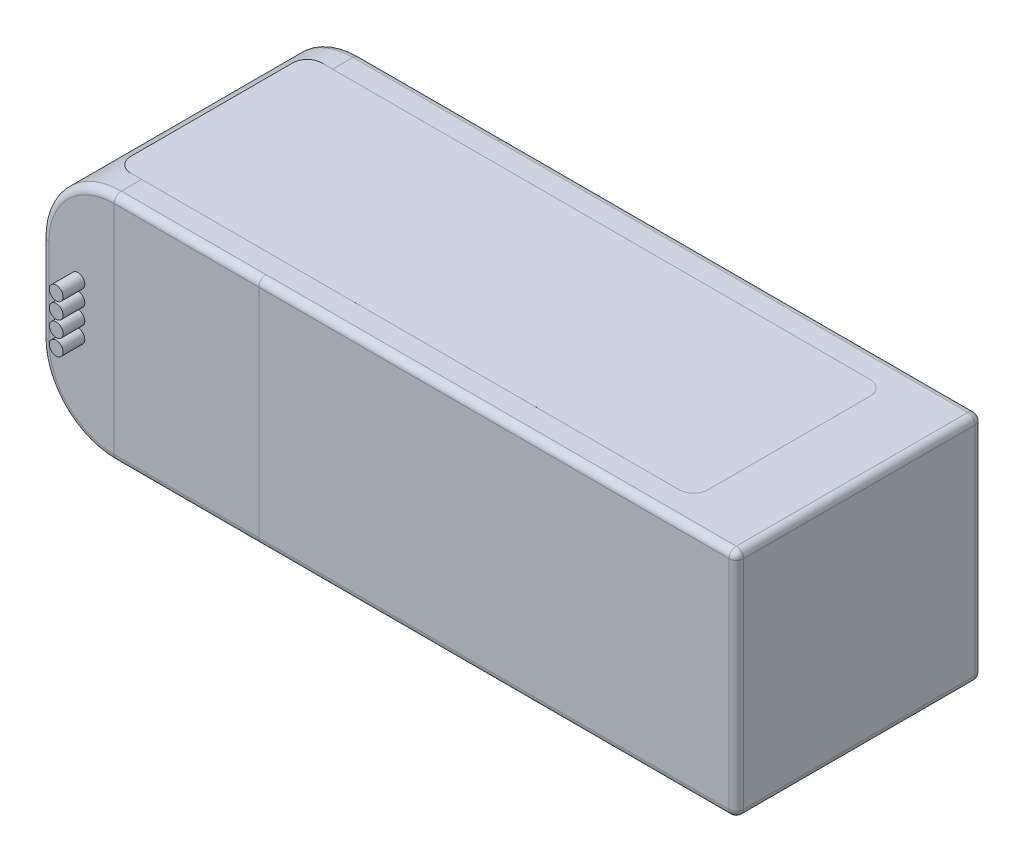
SolidWorks part; units mm, degrees
material "1060 Alloy"
ref_plane "Plano frontal" through (0, 0, 0) normal (0, 0, 1) x (1, 0, 0)
ref_plane "Plano superior" through (0, 0, 0) normal (0, 1, 0) x (1, 0, 0)
ref_plane "Plano direito" through (0, 0, 0) normal (1, 0, 0) x (0, 0, -1)
sketch "Sketch1" plane through (0, 0, 0) normal (0, 1, 0) x (1, 0, 0)
  line L1 (-48, 17) -> (48, 17)
  line L2 (-48, 17) -> (-48, -17)
  line L3 (-48, -17) -> (48, -17)
  line L4 (48, 17) -> (48, -17)
  point P4 (0, 17)
  point P6 (-48, 0)
  dimension "D1" = 34
  dimension "D2" = 96
extrude "Boss-Extrude1" add sketch "Sketch1" along normal mid plane 32
fillet "Fillet1" radius 10 2 edges at (-48, -16, 0) (-48, 16, 0)
sketch "Sketch2" plane through (0, 0, -17) normal (0, 0, -1) x (-1, 0, 0)
  line L1 (40, 1.45) -> (40, -1.45) construction
  line L2 (48, 6) -> (48, -6) construction
  circle A0 centre (40, 3.35) radius 1.9
  circle A1 centre (40, -3.35) radius 1.9
  point P4 (40, 0)
  dimension "D1" = 3.8
  dimension "D2" = 2.9
  dimension "D3" = 8
extrude "Boss-Extrude2" add sketch "Sketch2" along normal blind 5
sketch "Sketch4" plane through (0, 0, 17) normal (0, 0, 1) x (1, 0, 0)
  line L0 (-43, 4.25) -> (-43, -4.25) construction
  line L1 (-48, 6) -> (-48, -6) construction
  circle A0 centre (-43, 3.3) radius 0.95
  circle A1 centre (-43, 1.1) radius 0.95
  circle A2 centre (-43, -1.1) radius 0.95
  circle A3 centre (-43, -3.3) radius 0.95
  point P2 (-43, 0)
  dimension "D1" = 1.9
  dimension "D3" = 5
  dimension "D4" = 0.3
  dimension "D2" = 4
extrude "Boss-Extrude3" add sketch "Sketch4" along normal blind 3
sketch "Sketch5" plane through (0, 0, 17) normal (0, 0, 1) x (1, 0, 0)
  line L0 (-38, -16) -> (48, -16) construction
  line L1 (-38, 16) -> (-18, 16)
  line L2 (-38, 16) -> (-38, -16)
  line L3 (-38, -16) -> (-18, -16)
  line L4 (-18, 16) -> (-18, -16)
  dimension "D1" = 20
extrude "Boss-Extrude4" add sketch "Sketch5" along normal blind 0.0001
mirror "Mirror1" about plane through (0, 0, 0) normal (0, 0, 1) of "Boss-Extrude4" second plane through (0, 0, 0) second plane normal (0, 1, 0)
sketch "Sketch6" plane through (0, 16, 0) normal (0, 1, 0) x (1, 0, 0)
  line L0 (48, -17) -> (48, 17) construction
  line L1 (-39.5, 13.2) -> (36.3, 13.2)
  line L2 (-41.5, 11.2) -> (-41.5, -11.2)
  line L3 (-39.5, -13.2) -> (36.3, -13.2)
  line L4 (38.3, 11.2) -> (38.3, -11.2)
  arc A0 (36.3, 13.2) -> (38.3, 11.2) centre (36.3, 11.2) cw
  arc A1 (36.3, -13.2) -> (38.3, -11.2) centre (36.3, -11.2) ccw
  arc A2 (-41.5, -11.2) -> (-39.5, -13.2) centre (-39.5, -11.2) ccw
  arc A3 (-39.5, 13.2) -> (-41.5, 11.2) centre (-39.5, 11.2) ccw
  point P4 (-41.5, 0)
  point P10 (38.3, 13.2)
  point P15 (-41.5, -13.2)
  point P18 (-41.5, 13.2)
  dimension "D4" = 2
  dimension "D1" = 79.8
  dimension "D2" = 26.4
  dimension "D3" = 9.7
extrude "Boss-Extrude5" add sketch "Sketch6" along normal blind 0.0001
sketch "Sketch7" plane through (0, -16, 0) normal (0, -1, 0) x (1, 0, 0)
  line L0 (48, 17) -> (48, -17) construction
  line L1 (-27.6, 12.5) -> (23.3, 12.5)
  line L2 (-29.6, 10.5) -> (-29.6, -10.5)
  line L3 (-27.6, -12.5) -> (23.3, -12.5)
  line L4 (25.3, 10.5) -> (25.3, -10.5)
  arc A0 (23.3, -12.5) -> (25.3, -10.5) centre (23.3, -10.5) ccw
  arc A1 (23.3, 12.5) -> (25.3, 10.5) centre (23.3, 10.5) cw
  arc A2 (-29.6, -10.5) -> (-27.6, -12.5) centre (-27.6, -10.5) ccw
  arc A3 (-27.6, 12.5) -> (-29.6, 10.5) centre (-27.6, 10.5) ccw
  point P12 (-29.6, 0)
  dimension "D1" = 2
  dimension "D2" = 54.9
  dimension "D3" = 25
  dimension "D4" = 22.7
extrude "Boss-Extrude6" add sketch "Sketch7" along normal blind 0.0001
fillet "Fillet7" radius 1 14 edges at (-45.0711, 13.0711, 17) (-48, 0, 17) (-45.0711, 13.0711, -17) (-48, 0, -17) (48, 0, 17) (48, -16, 0) (48, 16, 0) (48, 0, -17) (15, -16, -17) (15, 16, -17) (15, -16, 17) (15, 16, 17) (-45.0711, -13.0711, 17) (-45.0711, -13.0711, -17)
fillet "Fillet8" radius 1 12 edges at (-38, 16, 16.5001) (-38, -16, 16.5001) (-18, -16, 16.5001) (-18, 16, 16.5001) (-28, -16, 17.0001) (-28, 16, 17.0001) (-38, -16, -16.5) (-28, 16, -17.0001) (-38, 16, -16.5) (-18, 16, -16.5) (-28, -16, -17.0001) (-18, -16, -16.5)
